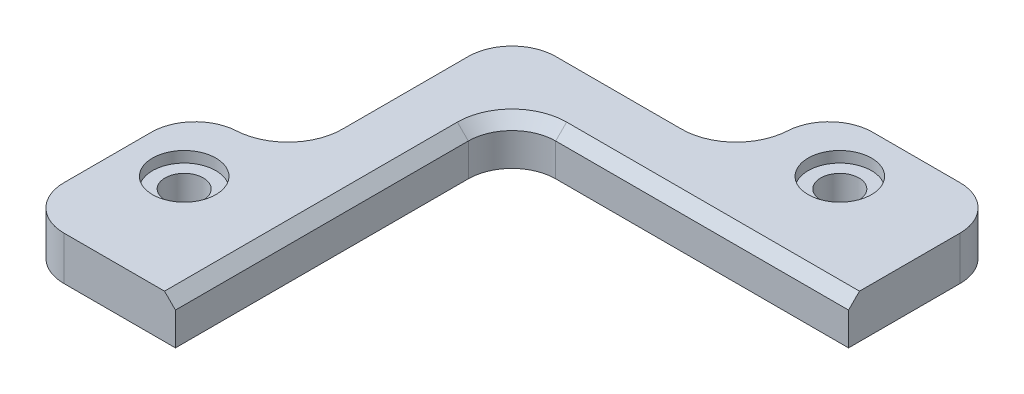
SolidWorks part; units mm, degrees
ref_plane "Alzado" through (0, 0, 0) normal (0, 0, 1) x (1, 0, 0)
ref_plane "Planta" through (0, 0, 0) normal (0, 1, 0) x (1, 0, 0)
ref_plane "Vista lateral" through (0, 0, 0) normal (1, 0, 0) x (0, 0, -1)
sketch "Croquis1" plane through (0, 0, 0) normal (0, 1, 0) x (1, 0, 0)
  line L0 (0, 0) -> (0, 45)
  line L1 (0, 45) -> (45, 45)
  line L2 (45, 45) -> (45, 35)
  line L3 (45, 35) -> (10, 35)
  line L4 (10, 35) -> (10, 0)
  line L5 (10, 0) -> (0, 0)
  line L6 (5, 0) -> (5, 45) construction
  line L7 (45, 40) -> (0, 40) construction
  circle A0 centre (35, 40) radius 1.75
  circle A1 centre (5, 10) radius 1.75
  dimension "D3" = 3.5
  dimension "D4" = 3.5
  dimension "D1" = 10
  dimension "D2" = 10
  dimension "D5" = 30
  dimension "D6" = 30
  dimension "D7" = 45
  dimension "D8" = 45
extrude "Saliente-Extruir1" add sketch "Croquis1" along normal blind 4
sketch "Croquis2" plane through (0, 4, 0) normal (0, 1, 0) x (1, 0, 0)
  line L0 (10, 35) -> (45, 35) construction
  line L1 (10, 0) -> (14.2, 0)
  line L2 (10, 0) -> (10, 35)
  line L3 (10, 35) -> (14.2, 35)
  line L4 (14.2, 0) -> (14.2, 35)
  line L6 (45, 35) -> (14.2, 35)
  line L7 (45, 35) -> (45, 30.8)
  line L8 (45, 30.8) -> (14.2, 30.8)
  line L9 (14.2, 35) -> (14.2, 30.8)
  line M6 (10, 0) -> (10, 35)
  line M7 (10, 35) -> (45, 35)
  dimension "D1" = 4.2
  dimension "D2" = 4.2
extrude "Saliente-Extruir2" add sketch "Croquis2" against normal up to surface (4 mm away) contours L8 L7 L4 M7 | L1 L4 M7 M6 up to face at (35, 0, -38.25)
sketch "Croquis3" plane through (0, 4, 0) normal (0, 1, 0) x (1, 0, 0)
  line L1 (0, 45) -> (29, 45)
  line L2 (0, 45) -> (0, 36.5)
  line L3 (0, 36.5) -> (29, 36.5)
  line L4 (29, 45) -> (29, 36.5)
  line L5 (0, 36.5) -> (8.5, 36.5)
  line L6 (0, 36.5) -> (0, 16)
  line L7 (0, 16) -> (8.5, 16)
  line L8 (8.5, 36.5) -> (8.5, 16)
  line M9 (45, 45) -> (0, 45)
  line M10 (0, 45) -> (0, 0)
  dimension "D1" = 8.5
  dimension "D2" = 29
  dimension "D3" = 8.5
  dimension "D4" = 20.5
extrude "Cortar-Extruir1" cut sketch "Croquis3" against normal up to surface (4 mm away) contours L4 L3 M9 M10 | L8 L3 L7 M10 up to face at (35, 0, -38.25)
fillet "Redondeo1" radius 4 2 edges at (14.2, 2, -30.8) (8.5, 2, -36.5)
fillet "Redondeo2" radius 4 4 edges at (0, 2, 0) (0, 2, -16) (29, 2, -45) (45, 2, -45)
chamfer "Chaflán1" distance 1 angle 45 3 edges at (14.2, 4, -13.4) (15.3716, 4, -29.6284) (31.6, 4, -30.8)
sketch "Croquis4" plane through (0, 4, 0) normal (0, 1, 0) x (1, 0, 0)
  circle A0 centre (35, 40) radius 2.9
  circle A1 centre (5, 10) radius 2.9
  dimension "D1" = 5.8
  dimension "D2" = 5.8
extrude "Cortar-Extruir2" cut sketch "Croquis4" against normal blind 1
fillet "Redondeo3" radius 5 2 edges at (8.5, 2, -16) (29, 2, -36.5)
